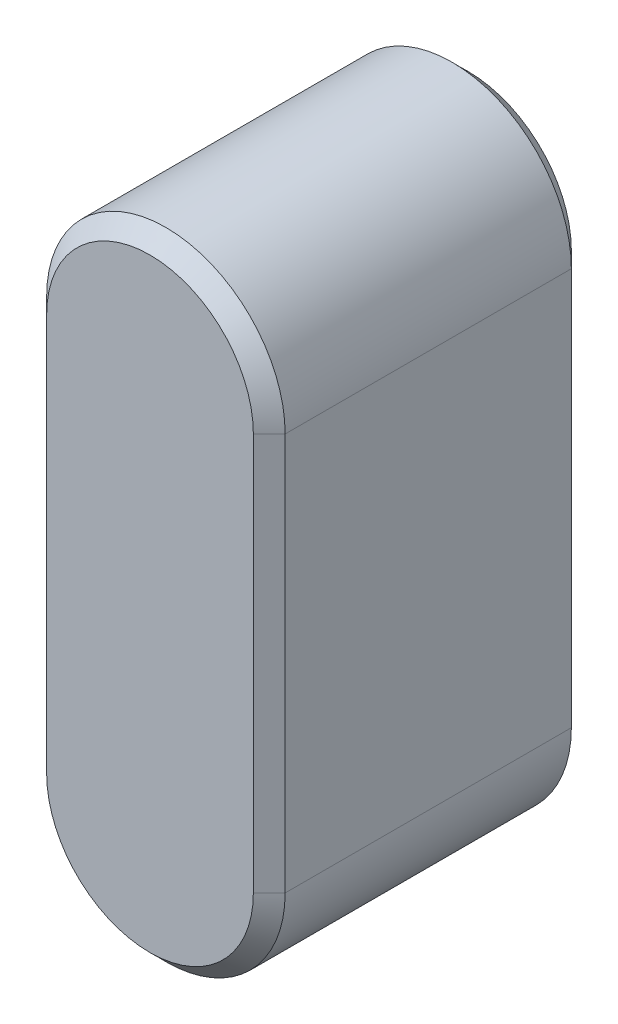
SolidWorks part; units mm, degrees
ref_plane "前视基准面" through (0, 0, 0) normal (0, 0, 1) x (1, 0, 0)
ref_plane "上视基准面" through (0, 0, 0) normal (0, 1, 0) x (1, 0, 0)
ref_plane "右视基准面" through (0, 0, 0) normal (1, 0, 0) x (0, 0, -1)
sketch "草图1" plane through (0, 0, 0) normal (0, 0, 1) x (1, 0, 0)
  line L0 (0, -2.5) -> (0, 2.5) construction
  line L1 (-1.5, -2.5) -> (-1.5, 2.5)
  line L2 (1.5, -2.5) -> (1.5, 2.5)
  arc A0 (-1.5, -2.5) -> (1.5, -2.5) centre (0, -2.5) ccw
  arc A1 (1.5, 2.5) -> (-1.5, 2.5) centre (0, 2.5) ccw
  point P2 (0, 0)
  dimension "D1" = 3
  dimension "D2" = 5
extrude "凸台-拉伸1" add sketch "草图1" along normal blind 4
chamfer "倒角1" distance 0.2 angle 45 8 edges at (-1.5, 0, 0) (0, -4, 0) (1.5, 0, 0) (0, 4, 0) (-1.5, 0, 4) (0, -4, 4) (1.5, 0, 4) (0, 4, 4)
